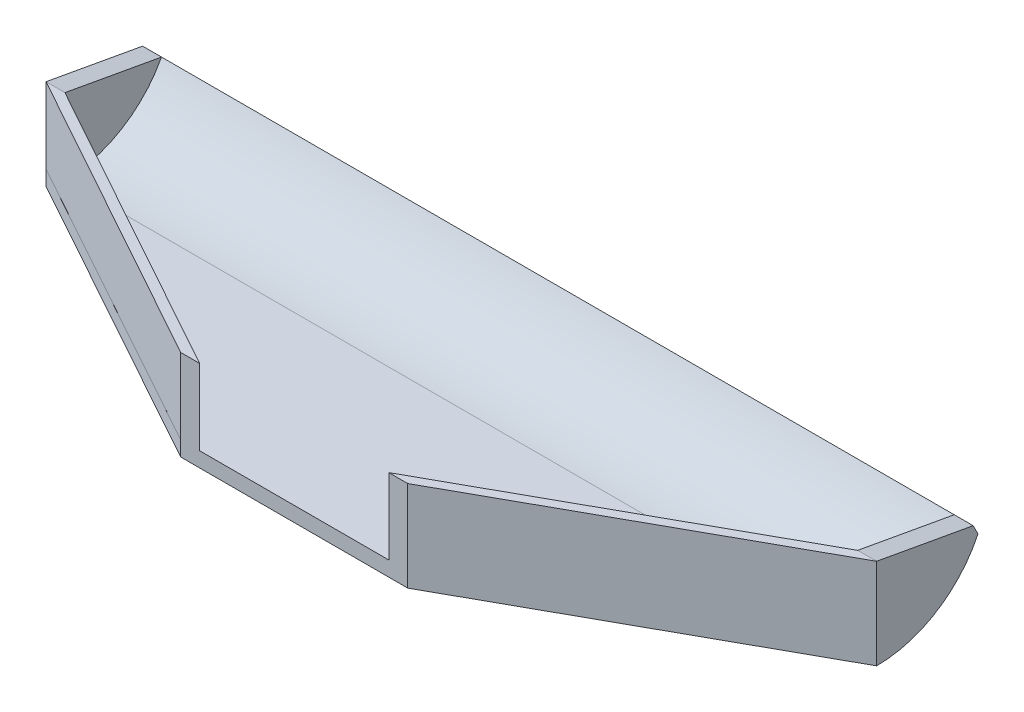
SolidWorks part; units mm, degrees
ref_plane "Front Plane" through (0, 0, 0) normal (0, 0, 1) x (1, 0, 0)
ref_plane "Top Plane" through (0, 0, 0) normal (0, 1, 0) x (1, 0, 0)
ref_plane "Right Plane" through (0, 0, 0) normal (1, 0, 0) x (0, 0, -1)
sketch "Sketch4" plane through (0, 0, 0) normal (1, 0, 0) x (0, 0, -1)
  line L1 (-159.8918, -100.9504) -> (-425.7918, -100.9504)
  line L8 (0, 0) -> (-7.6429, 15)
  line L11 (-160.8249, -77.2976) -> (-425.7918, -77.2976)
  line L12 (-425.7918, -100.9504) -> (-425.7918, -77.2976)
  arc A4 (0, 0) -> (-159.8918, -100.9504) centre (-159.8918, 76.1483) cw
  arc A6 (-7.6429, 15) -> (-160.8249, -77.2976) centre (-160.8249, 95.9657) cw
  dimension "D1" = 265.9
  dimension "D2" = 15
extrude "Boss-Extrude1" add sketch "Sketch4" along normal blind 1317.1
sketch "Sketch10" plane through (0, -77.2976, 0) normal (0, 1, 0) x (1, 0, 0)
  line L0 (478.6, -425.7918) -> (838.6, -425.7918)
  line L1 (1317.1, -425.7918) -> (0, -425.7918) construction
  line L2 (0, -160.8249) -> (0, -425.7918) construction
  line L3 (478.6, -425.7918) -> (0, -160.8249)
  line L4 (0, -160.8249) -> (0, -425.7918)
  line L5 (0, -425.7918) -> (478.6, -425.7918)
  line L6 (838.6, -425.7918) -> (1317.1, -160.8249)
  line L7 (1317.1, -160.8249) -> (1317.1, -425.7918)
  line L8 (1317.1, -425.7918) -> (838.6, -425.7918)
  line M2 (0, -160.8249) -> (0, -425.7918)
  line M3 (0, -425.7918) -> (1317.1, -425.7918)
  line M4 (1317.1, -425.7918) -> (1317.1, -160.8249)
  dimension "D1" = 360
  dimension "D2" = 478.6
extrude "Cut-Extrude3" cut sketch "Sketch10" against normal through all contours L3 M3 M2 | L6 M3 M4
sketch "Sketch11" plane through (0, -77.2976, 0) normal (0, 1, 0) x (1, 0, 0)
  line L0 (838.6, -425.7918) -> (808.6, -425.7918)
  line L1 (838.6, -425.7918) -> (478.6, -425.7918) construction
  line L2 (808.6, -425.7918) -> (1287.1, -160.8249)
  line L3 (1317.1, -160.8249) -> (0, -160.8249) construction
  line L4 (1287.1, -160.8249) -> (1317.1, -160.8249)
  line L5 (838.6, -425.7918) -> (1317.1, -160.8249)
  line L6 (658.6, -425.7918) -> (658.6, 347.5822) construction
  line L7 (478.6, -425.7918) -> (508.6, -425.7918)
  line L8 (508.6, -425.7918) -> (30.1, -160.8249)
  line L9 (30.1, -160.8249) -> (0.1, -160.8249)
  line L10 (478.6, -425.7918) -> (0.1, -160.8249)
  dimension "D1" = 30
  dimension "D2" = 30
extrude "Boss-Extrude5" add sketch "Sketch11" along normal blind 120
sketch "Sketch12" plane through (1317.1, 0, 0) normal (1, 0, 0) x (0, 0, -1)
  line L0 (-7.6429, 15) -> (-160.8249, 42.7024)
  line L1 (-160.8249, 42.7024) -> (-160.8249, -77.2976)
  arc A0 (-160.8249, -77.2976) -> (-7.6429, 15) centre (-160.8249, 95.9657) ccw
sketch "Sketch13" plane through (0, 0, 0) normal (1, 0, 0) x (0, 0, -1)
  line L0 (-7.6429, 15) -> (-160.8249, 42.7024)
  line L1 (-160.8249, 42.7024) -> (-160.8249, -77.2976)
  arc A0 (-7.6429, 15) -> (-160.8249, -77.2976) centre (-160.8249, 95.9657) cw
extrude "Boss-Extrude6" add sketch "Sketch13" along normal blind 30
extrude "Boss-Extrude7" add sketch "Sketch12" against normal blind 30
